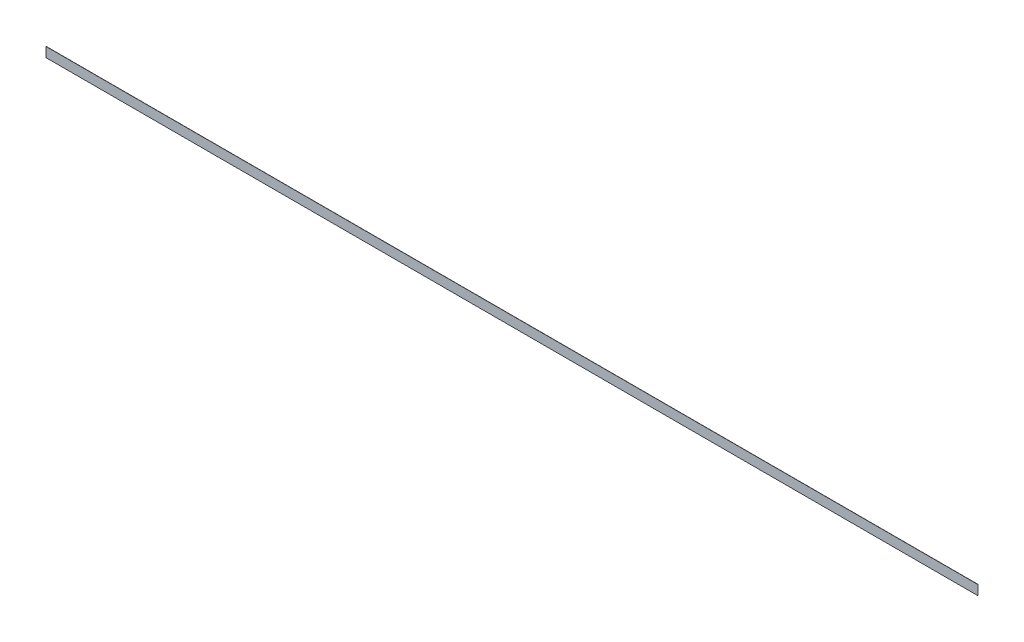
SolidWorks part; units mm, degrees
ref_plane "Front Plane" through (0, 0, 0) normal (0, 0, 1) x (1, 0, 0)
ref_plane "Top Plane" through (0, 0, 0) normal (0, 1, 0) x (1, 0, 0)
ref_plane "Right Plane" through (0, 0, 0) normal (1, 0, 0) x (0, 0, -1)
sketch "Sketch1" plane through (0, 0, 0) normal (0, 0, 1) x (1, 0, 0)
  line L1 (0, 0) -> (480, 0)
  line L2 (0, 0) -> (0, -5)
  line L3 (0, -5) -> (480, -5)
  line L4 (480, 0) -> (480, -5)
  dimension "D1" = 5
  dimension "D2" = 480
extrude "Boss-Extrude1" add sketch "Sketch1" along normal blind 0.1
